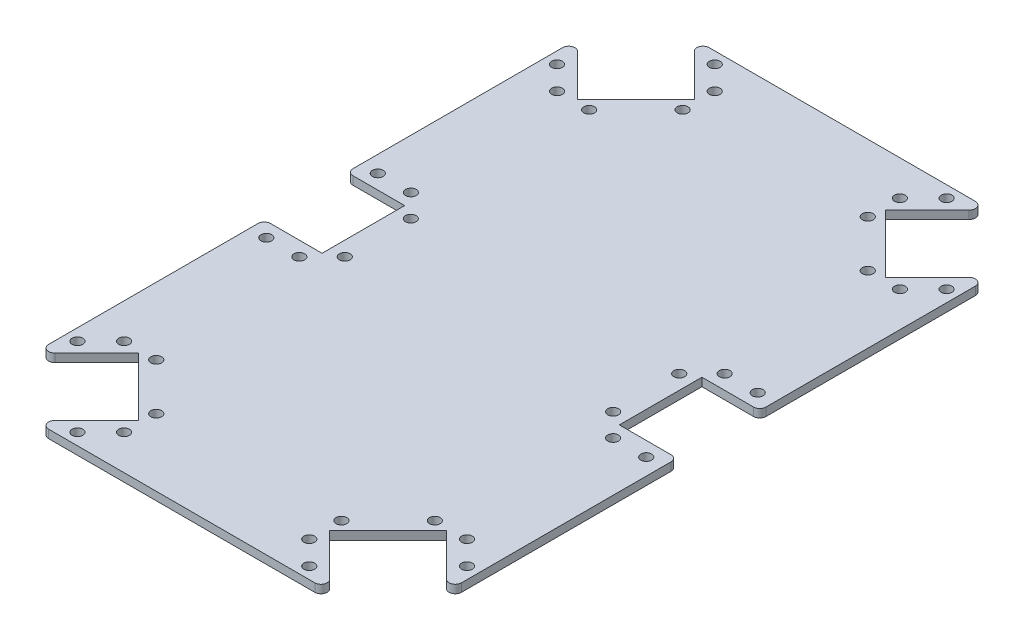
SolidWorks part; units mm, degrees
ref_plane "Front Plane" through (0, 0, 0) normal (0, 0, 1) x (1, 0, 0)
ref_plane "Top Plane" through (0, 0, 0) normal (0, 1, 0) x (1, 0, 0)
ref_plane "Right Plane" through (0, 0, 0) normal (1, 0, 0) x (0, 0, -1)
sketch "Sketch2" plane through (0, 0, 0) normal (0, 1, 0) x (1, 0, 0)
  line L0 (-50, 0) -> (50, 0) construction
  line L1 (-50, 80) -> (50, 80)
  line L2 (-50, 80) -> (-50, -80)
  line L3 (-50, -80) -> (50, -80)
  line L4 (50, 80) -> (50, -80)
  line L5 (50, 80) -> (0, 30) construction
  line L7 (0, 80) -> (0, -80) construction
  line L8 (22.4228, 63.7365) -> (18.5337, 67.6256) construction
  line L9 (18.5337, 67.6256) -> (22.4228, 71.5147) construction
  line L10 (22.4228, 71.5147) -> (28.0797, 77.1716) construction
  line L11 (28.0797, 77.1716) -> (30.9081, 80) construction
  circle A5 centre (22.4228, 63.7365) radius 1.3
  circle A6 centre (22.4228, 71.5147) radius 1.3
  circle A7 centre (28.0797, 77.1716) radius 1.3
  circle A8 centre (46, 13.5) radius 1.3
  circle A9 centre (38, 13.5) radius 1.3
  circle A10 centre (32.5, 8) radius 1.3
  circle A11 centre (32.5, -8) radius 1.3
  circle A12 centre (38, -13.5) radius 1.3
  circle A13 centre (46, -13.5) radius 1.3
  circle A14 centre (47.1716, 58.0797) radius 1.3
  circle A15 centre (41.5147, 52.4228) radius 1.3
  circle A16 centre (33.7365, 52.4228) radius 1.3
  circle A17 centre (47.1716, -58.0797) radius 1.3
  circle A18 centre (41.5147, -52.4228) radius 1.3
  circle A19 centre (33.7365, -52.4228) radius 1.3
  circle A20 centre (28.0797, -77.1716) radius 1.3
  circle A21 centre (22.4228, -71.5147) radius 1.3
  circle A22 centre (22.4228, -63.7365) radius 1.3
  circle A23 centre (-28.0797, 77.1716) radius 1.3
  circle A24 centre (-22.4228, 71.5147) radius 1.3
  circle A25 centre (-22.4228, 63.7365) radius 1.3
  circle A26 centre (-47.1716, 58.0797) radius 1.3
  circle A27 centre (-41.5147, 52.4228) radius 1.3
  circle A28 centre (-33.7365, 52.4228) radius 1.3
  circle A29 centre (-47.1716, -58.0797) radius 1.3
  circle A30 centre (-41.5147, -52.4228) radius 1.3
  circle A31 centre (-33.7365, -52.4228) radius 1.3
  circle A32 centre (-22.4228, -63.7365) radius 1.3
  circle A33 centre (-22.4228, -71.5147) radius 1.3
  circle A34 centre (-28.0797, -77.1716) radius 1.3
  circle A35 centre (-32.5, -8) radius 1.3
  circle A36 centre (-38, -13.5) radius 1.3
  circle A37 centre (-46, -13.5) radius 1.3
  circle A38 centre (-46, 13.5) radius 1.3
  circle A39 centre (-38, 13.5) radius 1.3
  circle A40 centre (-32.5, 8) radius 1.3
  point P0 (0, 0)
  point P24 (0, 0)
  point P26 (0, 0)
  point P27 (0, 0)
  point P40 (32.7378, 8)
  point P41 (0, 0)
  point P42 (0, 0)
  dimension "D6" = 5.5
  dimension "D10" = 8
  dimension "D11" = 5.5
  dimension "D2" = 2.6
  dimension "D3" = 8
  dimension "D4" = 4
  dimension "D5" = 5.5
  dimension "D7" = 45
  dimension "D8" = 100
  dimension "D9" = 160
  dimension "D12" = 5.5
  dimension "D13" = 8
  dimension "D14" = 4
  dimension "D15" = 8
extrude "Boss-Extrude1" add sketch "Sketch2" along normal blind 2
sketch "Sketch3" plane through (0, 2, 0) normal (0, 1, 0) x (1, 0, 0)
  line L0 (0, -80) -> (0, 80) construction
  line L1 (-50, -80) -> (50, -80) construction
  line L2 (50, 80) -> (-50, 80) construction
  line L3 (-50, 0) -> (50, 0) construction
  line L4 (-50, 80) -> (-50, -80) construction
  line L5 (50, -80) -> (50, 80) construction
  line L6 (50, 80) -> (0, 30) construction
  line L7 (50, -10) -> (36, -10)
  line L8 (50, -10) -> (50, 10)
  line L9 (50, 10) -> (36, 10)
  line L10 (36, -10) -> (36, 10)
  line L11 (35.8579, 80) -> (23.1299, 67.2721)
  line L12 (23.1299, 67.2721) -> (37.2721, 53.1299)
  line L13 (37.2721, 53.1299) -> (50, 65.8579)
  line L14 (50, 65.8579) -> (50, 80)
  line L15 (50, 80) -> (35.8579, 80)
  line L16 (50, -65.8579) -> (50, -80)
  line L17 (37.2721, -53.1299) -> (50, -65.8579)
  line L18 (23.1299, -67.2721) -> (37.2721, -53.1299)
  line L19 (35.8579, -80) -> (23.1299, -67.2721)
  line L20 (50, -80) -> (35.8579, -80)
  line L21 (-50, 65.8579) -> (-50, 80)
  line L22 (-37.2721, 53.1299) -> (-50, 65.8579)
  line L23 (-23.1299, 67.2721) -> (-37.2721, 53.1299)
  line L24 (-35.8579, 80) -> (-23.1299, 67.2721)
  line L25 (-50, 80) -> (-35.8579, 80)
  line L26 (-50, 10) -> (-36, 10)
  line L27 (-36, -10) -> (-36, 10)
  line L28 (-50, -10) -> (-36, -10)
  line L29 (-50, -10) -> (-50, 10)
  line L30 (-37.2721, -53.1299) -> (-50, -65.8579)
  line L31 (-23.1299, -67.2721) -> (-37.2721, -53.1299)
  line L32 (-35.8579, -80) -> (-23.1299, -67.2721)
  line L33 (-50, -80) -> (-35.8579, -80)
  line L34 (-50, -65.8579) -> (-50, -80)
  dimension "D1" = 10
  dimension "D2" = 20
  dimension "D3" = 14
  dimension "D4" = 45
  dimension "D5" = 18
  dimension "D6" = 20
  dimension "D7" = 10
extrude "Cut-Extrude1" cut sketch "Sketch3" against normal up to surface (2 mm away) up to face at (0, 0, 0)
fillet "Fillet1" radius 1.5 12 edges at (-50, 1, 10) (-50, 1, -10) (-50, 1, 65.8579) (-35.8579, 1, 80) (35.8579, 1, 80) (50, 1, 65.8579) (50, 1, 10) (50, 1, -10) (50, 1, -65.8579) (35.8579, 1, -80) (-50, 1, -65.8579) (-35.8579, 1, -80)
